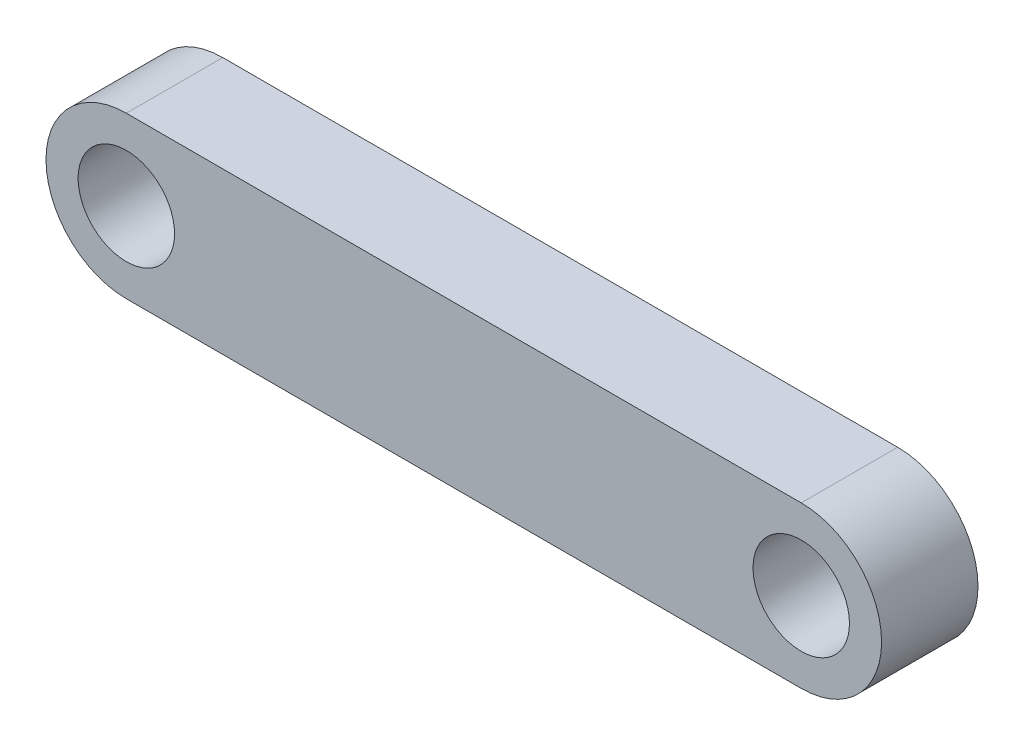
SolidWorks part; units mm, degrees
ref_plane "Front Plane" through (0, 0, 0) normal (0, 0, 1) x (1, 0, 0)
ref_plane "Top Plane" through (0, 0, 0) normal (0, 1, 0) x (1, 0, 0)
ref_plane "Right Plane" through (0, 0, 0) normal (1, 0, 0) x (0, 0, -1)
sketch "Sketch1" plane through (0, 0, 0) normal (0, 0, 1) x (1, 0, 0)
  line L0 (0, 0) -> (21, 0)
  line L1 (0, 5) -> (21, 5)
  line L2 (0, 5) -> (0, 0) construction
  line L3 (21, 5) -> (21, 0) construction
  arc A0 (0, 5) -> (0, 0) centre (0, 2.5) ccw
  arc A1 (21, 5) -> (21, 0) centre (21, 2.5) cw
  circle A2 centre (0, 2.5) radius 1.5
  circle A3 centre (21, 2.5) radius 1.5
  dimension "D2" = 3
  dimension "D4" = 3
  dimension "D1" = 5
  dimension "D3" = 21
extrude "Boss-Extrude1" add sketch "Sketch1" along normal blind 3
